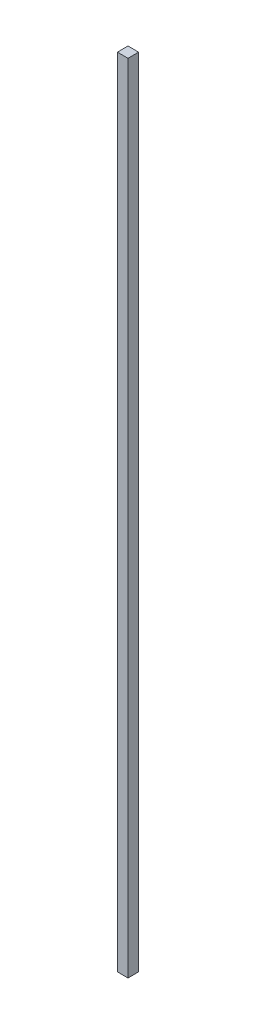
SolidWorks part; units mm, degrees
ref_plane "Спереди" through (0, 0, 0) normal (0, 0, 1) x (1, 0, 0)
ref_plane "Сверху" through (0, 0, 0) normal (0, 1, 0) x (1, 0, 0)
ref_plane "Справа" through (0, 0, 0) normal (1, 0, 0) x (0, 0, -1)
sketch "Эскиз1" plane through (0, 0, 0) normal (0, 1, 0) x (1, 0, 0)
  line L1 (-16.0788, 23.2728) -> (23.9212, 23.2728)
  line L2 (-16.0788, 23.2728) -> (-16.0788, -16.7272)
  line L3 (-16.0788, -16.7272) -> (23.9212, -16.7272)
  line L4 (23.9212, 23.2728) -> (23.9212, -16.7272)
extrude "Бобышка-Вытянуть1" add sketch "Эскиз1" along normal blind 3000
